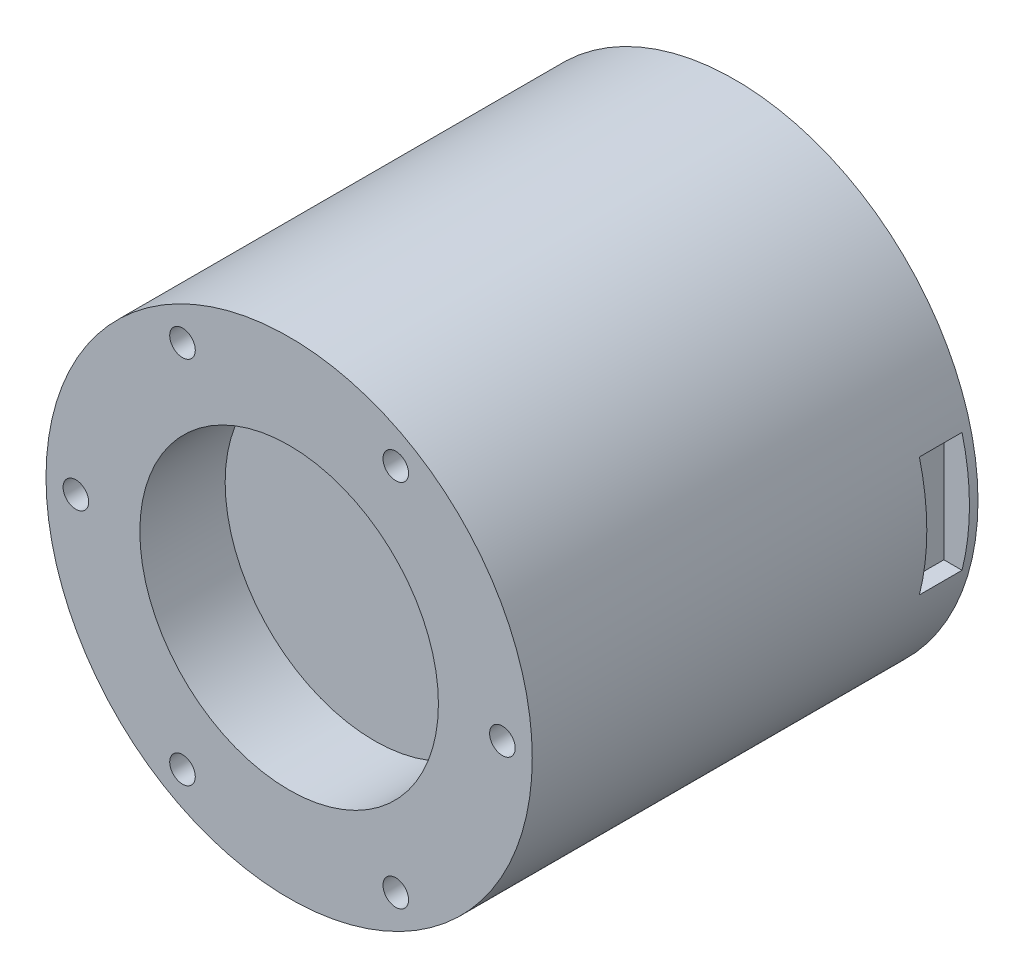
SolidWorks part; units mm, degrees
ref_plane "前视基准面" through (0, 0, 0) normal (0, 0, 1) x (1, 0, 0)
ref_plane "上视基准面" through (0, 0, 0) normal (0, 1, 0) x (1, 0, 0)
ref_plane "右视基准面" through (0, 0, 0) normal (1, 0, 0) x (0, 0, -1)
other "Configuration Table"
sketch "草图1" plane through (0, 0, 0) normal (0, 0, 1) x (1, 0, 0)
  circle A0 centre (0, 0) radius 28.5
  dimension "D1" = 57
extrude "凸台-拉伸1" add sketch "草图1" along normal blind 52.25
sketch "草图2" plane through (0, 0, 52.25) normal (0, 0, 1) x (1, 0, 0)
  circle A0 centre (25, 0) radius 1.5
  dimension "D1" = 3
  dimension "D2" = 25
extrude "切除-拉伸1" cut sketch "草图2" against normal blind 5
pattern_circular "阵列(圆周)1" count 6 over 360 about axis through (0, 0, 0) along (0, 0, 1) of "切除-拉伸1"
sketch "草图3" plane through (0, 0, 52.25) normal (0, 0, 1) x (1, 0, 0)
  circle A0 centre (0, 0) radius 17.5
  dimension "D1" = 35
extrude "切除-拉伸2" cut sketch "草图3" against normal blind 10
sketch "草图5" plane through (0, 0, 0) normal (0, 0, -1) x (-1, 0, 0)
  line L0 (35.2467, 0) -> (-32.0736, 0) construction
  line L1 (27.627, 7) -> (25.5, 7)
  line L2 (25.5, 7) -> (25.5, -7)
  line L3 (27.627, -7) -> (25.5, -7)
  line L4 (0, 33.9631) -> (0, -40.208) construction
  line L5 (-27.627, -7) -> (-25.5, -7)
  line L6 (-27.627, 7) -> (-25.5, 7)
  line L7 (-25.5, 7) -> (-25.5, -7)
  circle A0 centre (0, 0) radius 28.5 construction
  arc A1 (27.627, 7) -> (27.627, -7) centre (0, 0) cw
  arc A2 (-27.627, 7) -> (-27.627, -7) centre (0, 0) ccw
  point P10 (25.5, 0)
  circle M4 centre (0, 0) radius 28.5
  dimension "D1" = 7
  dimension "D2" = 25.5
extrude "切除-拉伸5" cut sketch "草图5" against normal blind 5 from offset 1 contours L3 L1 L2 M4 | L7 L6 L5 M4 offset against normal yes
sketch "草图7" plane through (0, 0, 0) normal (0, 0, -1) x (-1, 0, 0)
  line L0 (0, 31.189) -> (0, -35.5009) construction
  line L1 (-4, -28.2179) -> (-4, -25.5)
  line L2 (-4, -25.5) -> (4, -25.5)
  line L3 (4, -28.2179) -> (4, -25.5)
  circle A0 centre (0, 0) radius 28.5 construction
  arc A1 (4, -28.2179) -> (-4, -28.2179) centre (0, 0) cw
  point P9 (0, -25.5)
  circle M4 centre (0, 0) radius 28.5
  dimension "D1" = 4
  dimension "D2" = 25.5
extrude "切除-拉伸6" cut sketch "草图7" against normal blind 8 from offset 1 contours L2 L0 A1 L3 | L0 L2 L1 M4 offset against normal yes
sketch "草图8" plane through (0, 0, 0) normal (0, 0, -1) x (-1, 0, 0)
  line L0 (-33.9415, 0) -> (38.5205, 0) construction
  line L1 (0, 0) -> (22.6235, 22.6235) construction
  circle A0 centre (13.435, 13.435) radius 1.5
  dimension "D2" = 3
  dimension "D1" = 45
  dimension "D3" = 19
extrude "切除-拉伸8" cut sketch "草图8" against normal blind 4
pattern_circular "阵列(圆周)2" count 4 over 360 about axis through (0, 0, 0) along (0, 0, 1) of "切除-拉伸8"
